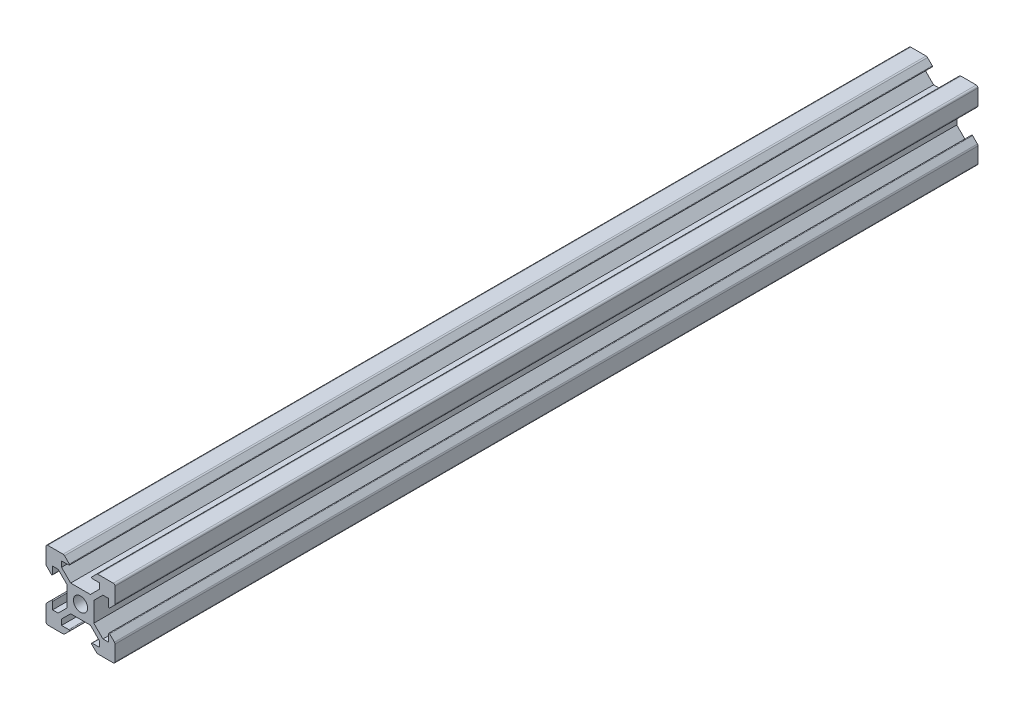
SolidWorks part; units mm, degrees
material "6063-T5"
ref_plane "Front Plane" through (0, 0, 0) normal (1, 0, 0) x (0, 1, 0)
ref_plane "Top Plane" through (0, 0, 0) normal (0, 0, 1) x (0, 1, 0)
ref_plane "Right Plane" through (0, 0, 0) normal (0, 1, 0) x (-1, 0, 0)
sketch "Sketch1" plane through (0, 0, 0) normal (0, 0, 1) x (0, 1, 0)
  line L0 (0, 0) -> (-10, 10) construction
  line L5 (-2.8601, -3.85) -> (2.8601, -3.85)
  line L6 (-3.85, -2.8601) -> (-3.85, 2.8601)
  line L11 (-2.8601, 3.85) -> (2.8601, 3.85)
  line L12 (3.85, -2.8601) -> (3.85, 2.8601)
  line L15 (-9.5, 10) -> (-5.0485, 10)
  line L16 (-4.6243, 9.8243) -> (-3.2414, 8.4414)
  line L17 (-3.3828, 8.1) -> (-5.5, 8.1)
  line L18 (-5.5, 8.1) -> (-5.5, 6.4899)
  line L19 (-5.5, 6.4899) -> (-2.8601, 3.85)
  line L20 (-6.4899, 5.5) -> (-3.85, 2.8601)
  line L21 (-10, 9.5) -> (-10, 5.0485)
  line L22 (-8.1, 5.5) -> (-6.4899, 5.5)
  line L23 (-8.1, 3.3828) -> (-8.1, 5.5)
  line L24 (-9.8243, 4.6243) -> (-8.4414, 3.2414)
  line L25 (10, 9.5) -> (10, 5.0485)
  line L26 (9.8243, 4.6243) -> (8.4414, 3.2414)
  line L27 (8.1, 3.3828) -> (8.1, 5.5)
  line L28 (8.1, 5.5) -> (6.4899, 5.5)
  line L29 (6.4899, 5.5) -> (3.85, 2.8601)
  line L30 (5.5, 6.4899) -> (2.8601, 3.85)
  line L31 (9.5, 10) -> (5.0485, 10)
  line L32 (5.5, 8.1) -> (5.5, 6.4899)
  line L33 (3.3828, 8.1) -> (5.5, 8.1)
  line L34 (4.6243, 9.8243) -> (3.2414, 8.4414)
  line L35 (9.5, -10) -> (5.0485, -10)
  line L36 (4.6243, -9.8243) -> (3.2414, -8.4414)
  line L37 (3.3828, -8.1) -> (5.5, -8.1)
  line L38 (5.5, -8.1) -> (5.5, -6.4899)
  line L39 (5.5, -6.4899) -> (2.8601, -3.85)
  line L40 (6.4899, -5.5) -> (3.85, -2.8601)
  line L41 (10, -9.5) -> (10, -5.0485)
  line L42 (8.1, -5.5) -> (6.4899, -5.5)
  line L43 (8.1, -3.3828) -> (8.1, -5.5)
  line L44 (9.8243, -4.6243) -> (8.4414, -3.2414)
  line L45 (-10, -9.5) -> (-10, -5.0485)
  line L46 (-9.8243, -4.6243) -> (-8.4414, -3.2414)
  line L47 (-8.1, -3.3828) -> (-8.1, -5.5)
  line L48 (-8.1, -5.5) -> (-6.4899, -5.5)
  line L49 (-6.4899, -5.5) -> (-3.85, -2.8601)
  line L50 (-5.5, -6.4899) -> (-2.8601, -3.85)
  line L51 (-9.5, -10) -> (-5.0485, -10)
  line L52 (-5.5, -8.1) -> (-5.5, -6.4899)
  line L53 (-3.3828, -8.1) -> (-5.5, -8.1)
  line L54 (-4.6243, -9.8243) -> (-3.2414, -8.4414)
  circle A1 centre (0, 0) radius 2.05
  arc A2 (-10, -9.5) -> (-9.5, -10) centre (-9.5, -9.5) ccw
  arc A3 (9.5, -10) -> (10, -9.5) centre (9.5, -9.5) ccw
  arc A4 (10, 9.5) -> (9.5, 10) centre (9.5, 9.5) ccw
  arc A5 (-10, 9.5) -> (-9.5, 10) centre (-9.5, 9.5) cw
  arc A6 (-3.2414, 8.4414) -> (-3.3828, 8.1) centre (-3.3828, 8.3) cw
  arc A7 (3.3828, 8.1) -> (3.2414, 8.4414) centre (3.3828, 8.3) cw
  arc A8 (8.4414, 3.2414) -> (8.1, 3.3828) centre (8.3, 3.3828) cw
  arc A9 (8.1, -3.3828) -> (8.4414, -3.2414) centre (8.3, -3.3828) cw
  arc A10 (3.2414, -8.4414) -> (3.3828, -8.1) centre (3.3828, -8.3) cw
  arc A11 (-3.3828, -8.1) -> (-3.2414, -8.4414) centre (-3.3828, -8.3) cw
  arc A12 (-8.4414, -3.2414) -> (-8.1, -3.3828) centre (-8.3, -3.3828) cw
  arc A13 (-8.1, 3.3828) -> (-8.4414, 3.2414) centre (-8.3, 3.3828) cw
  arc A14 (5.0485, 10) -> (4.6243, 9.8243) centre (5.0485, 9.4) ccw
  arc A15 (10, 5.0485) -> (9.8243, 4.6243) centre (9.4, 5.0485) cw
  arc A16 (10, -5.0485) -> (9.8243, -4.6243) centre (9.4, -5.0485) ccw
  arc A17 (5.0485, -10) -> (4.6243, -9.8243) centre (5.0485, -9.4) cw
  arc A18 (-5.0485, -10) -> (-4.6243, -9.8243) centre (-5.0485, -9.4) ccw
  arc A19 (-10, -5.0485) -> (-9.8243, -4.6243) centre (-9.4, -5.0485) cw
  arc A20 (-5.0485, 10) -> (-4.6243, 9.8243) centre (-5.0485, 9.4) cw
  arc A21 (-10, 5.0485) -> (-9.8243, 4.6243) centre (-9.4, 5.0485) ccw
  point P0 (0, 0)
  point P56 (0, 0)
  point P64 (-2.9, 8.1)
  point P79 (-8.1, 2.9)
  point P94 (-4.8, 10)
  point P97 (-10, 4.8)
  dimension "D3" = 7.7
  dimension "D2" = 4.1
  dimension "D9" = 0.5
  dimension "D10" = 0.2
  dimension "D11" = 0.6
  dimension "D1" = 10
  dimension "D4" = 7.1
  dimension "D5" = 1.4
  dimension "D6" = 4.5
  dimension "D7" = 1.9
  dimension "D8" = 4
extrude "Boss-Extrude1" add sketch "Sketch1" along normal blind 250
